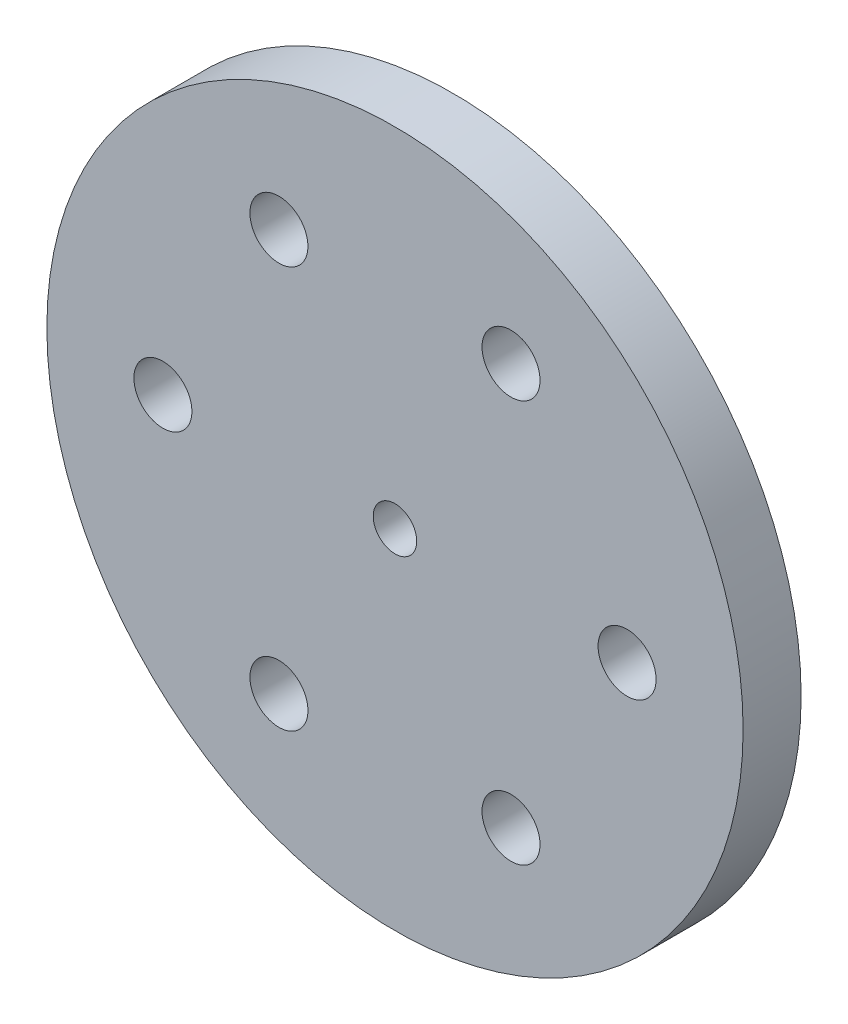
SolidWorks part; units mm, degrees
ref_plane "Front Plane" through (0, 0, 0) normal (0, 0, 1) x (1, 0, 0)
ref_plane "Top Plane" through (0, 0, 0) normal (0, 1, 0) x (1, 0, 0)
ref_plane "Right Plane" through (0, 0, 0) normal (1, 0, 0) x (0, 0, -1)
sketch "Sketch1" plane through (0, 0, 0) normal (0, 0, 1) x (1, 0, 0)
  line L0 (0, 0) -> (-25.4, 0) construction
  circle A0 centre (0, 0) radius 38.1
  circle A1 centre (0, 0) radius 25.4 construction
  point P18 (0, 0)
  dimension "D1" = 50.8
  dimension "D4" = 76.2
extrude "Boss-Extrude1" add sketch "Sketch1" along normal blind 6.35
sketch "Sketch2" plane through (0, 0, 6.35) normal (0, 0, 1) x (1, 0, 0)
  circle A1 centre (0, 0) radius 2.3813
  dimension "D1" = 4.7625
sketch "Sketch4" plane through (0, 0, 0) normal (0, 0, -1) x (-1, 0, 0)
  circle A0 centre (0, 0) radius 25.4 construction
  circle A1 centre (-25.4, 0) radius 3.175
  circle A2 centre (0, 0) radius 25.4 construction
  circle A3 centre (-12.7, 21.997) radius 3.175
  circle A4 centre (0, 0) radius 25.4 construction
  circle A5 centre (12.7, 21.997) radius 3.175
  circle A6 centre (0, 0) radius 25.4 construction
  circle A7 centre (25.4, 0) radius 3.175
  circle A8 centre (0, 0) radius 25.4 construction
  circle A9 centre (12.7, -21.997) radius 3.175
  circle A10 centre (0, 0) radius 25.4 construction
  circle A11 centre (-12.7, -21.997) radius 3.175
  point P23 (0, 0)
  dimension "D1" = 50.8
  dimension "D2" = 6.35
  dimension "D3" = 6
extrude "Cut-Extrude2" cut sketch "Sketch4" against normal through all
extrude "Cut-Extrude3" cut sketch "Sketch2" against normal through all
